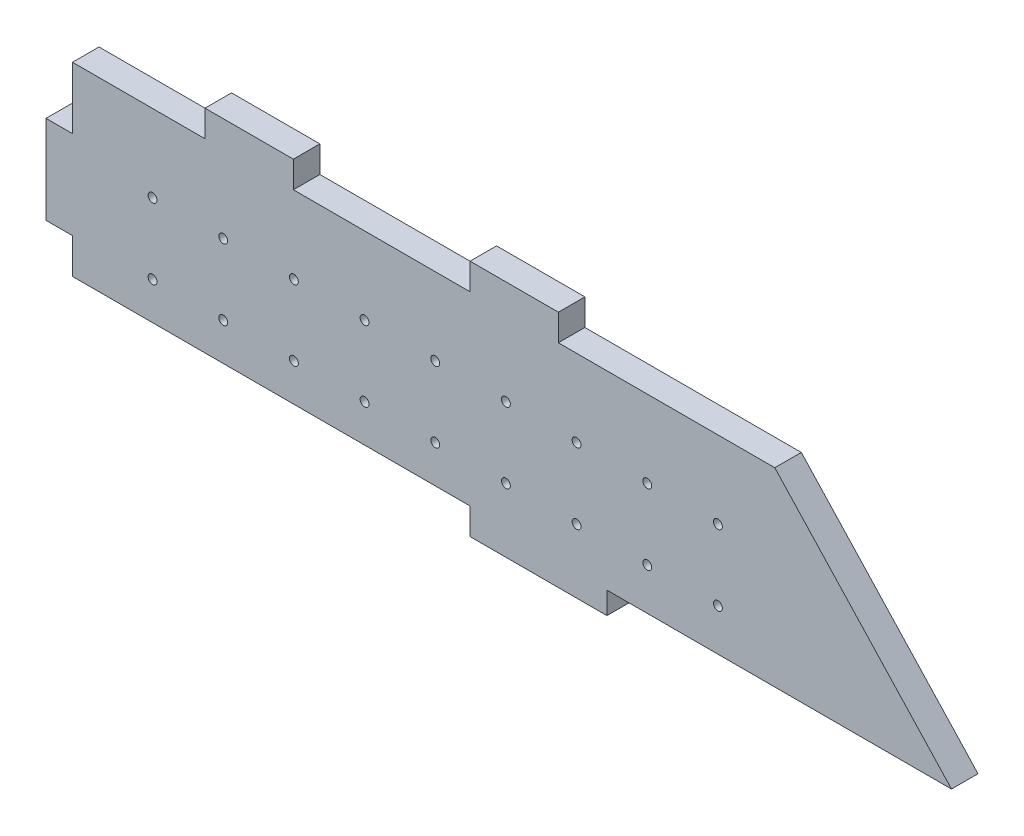
SolidWorks part; units mm, degrees
ref_plane "Plan de face" through (0, 0, 0) normal (0, 0, 1) x (1, 0, 0)
ref_plane "Plan de dessus" through (0, 0, 0) normal (0, 1, 0) x (1, 0, 0)
ref_plane "Plan de droite" through (0, 0, 0) normal (1, 0, 0) x (0, 0, -1)
sketch "Esquisse1" plane through (0, 0, 0) normal (0, 0, 1) x (1, 0, 0)
  line L1 (0, 0) -> (-199, 0)
  line L2 (0, 0) -> (0, 48)
  line L3 (0, 48) -> (-199, 48)
  line L4 (-199, 0) -> (-199, 48)
  dimension "D1" = 48
  dimension "D2" = 199
extrude "Boss.-Extru.1" add sketch "Esquisse1" along normal blind 6
sketch "Esquisse2" plane through (0, 48, 0) normal (0, 1, 0) x (1, 0, 0)
  line L0 (0, -6) -> (-199, -6) construction
  line L1 (-89, -6) -> (-109, -6)
  line L2 (-89, -6) -> (-89, 0)
  line L3 (-89, 0) -> (-109, 0)
  line L4 (-109, -6) -> (-109, 0)
  line L5 (0, 0) -> (-199, 0) construction
  line L6 (-199, -6) -> (-199, 0) construction
  line L7 (-149, -6) -> (-169, -6)
  line L8 (-149, -6) -> (-149, 0)
  line L9 (-149, 0) -> (-169, 0)
  line L10 (-169, -6) -> (-169, 0)
  dimension "D1" = 20
  dimension "D2" = 20
  dimension "D3" = 40
  dimension "D4" = 30
extrude "Boss.-Extru.2" add sketch "Esquisse2" along normal blind 6
sketch "Esquisse3" plane through (-199, 0, 0) normal (-1, 0, 0) x (0, 0, 1)
  line L1 (6, 48) -> (6, 0) construction
  line L2 (6, 34) -> (0, 34)
  line L3 (6, 34) -> (6, 14)
  line L4 (6, 14) -> (0, 14)
  line L6 (0, 34) -> (0, 14)
  line L7 (0, 48) -> (0, 0) construction
  line L8 (6, 48) -> (0, 48) construction
  dimension "D1" = 20
  dimension "D2" = 14
extrude "Boss.-Extru.3" add sketch "Esquisse3" along normal blind 6
sketch "Esquisse4" plane through (0, 0, 6) normal (0, 0, 1) x (1, 0, 0)
  line L1 (0, 0) -> (-78, 0)
  line L2 (0, 0) -> (0, 5)
  line L3 (0, 5) -> (-78, 5)
  line L4 (-78, 0) -> (-78, 5)
  dimension "D1" = 5
  dimension "D2" = 78
extrude "Enlèv. mat.-Extru.1" cut sketch "Esquisse4" against normal through all
sketch "Esquisse5" plane through (0, 0, 6) normal (0, 0, 1) x (1, 0, 0)
  line L0 (0, 48) -> (-40, 48)
  line L1 (0, 48) -> (-89, 48) construction
  line L2 (-40, 48) -> (0, 5)
  line L3 (0, 5) -> (0, 48)
  dimension "D1" = 159
extrude "Enlèv. mat.-Extru.2" cut sketch "Esquisse5" against normal through all
sketch "Esquisse6" plane through (0, 0, 6) normal (0, 0, 1) x (1, 0, 0)
  line L0 (-199, 0) -> (-78, 0) construction
  line L1 (-199, 14) -> (-199, 0) construction
  line L2 (-199, 48) -> (-199, 34) construction
  line L3 (-148.88, 14.5) -> (-164.88, 14.5) construction
  line L5 (-199, 0) -> (-78, 0) construction
  circle A0 centre (-148.88, 14.5) radius 1.005
  circle A1 centre (-148.88, 30.5) radius 1.005
  circle A2 centre (-132.88, 14.5) radius 1.005
  circle A3 centre (-132.88, 30.5) radius 1.005
  circle A4 centre (-116.88, 14.5) radius 1.005
  circle A5 centre (-116.88, 30.5) radius 1.005
  circle A6 centre (-100.88, 14.5) radius 1.005
  circle A7 centre (-100.88, 30.5) radius 1.005
  circle A8 centre (-84.88, 14.5) radius 1.005
  circle A9 centre (-84.88, 30.5) radius 1.005
  circle A10 centre (-68.88, 14.5) radius 1.005
  circle A11 centre (-68.88, 30.5) radius 1.005
  circle A12 centre (-52.88, 14.5) radius 1.005
  circle A13 centre (-52.88, 30.5) radius 1.005
  circle A14 centre (-164.88, 14.5) radius 1.005
  circle A15 centre (-164.88, 30.5) radius 1.005
  circle A16 centre (-180.88, 14.5) radius 1.005
  circle A17 centre (-180.88, 30.5) radius 1.005
  dimension "D1" = 2.01
  dimension "D2" = 2.01
  dimension "D3" = 2.01
  dimension "D4" = 2.01
  dimension "D12" = 50.12
  dimension "D16" = 14.5
  dimension "D17" = 14.5
  dimension "D18" = 16
  dimension "D5" = 16
  dimension "D6" = 16
  dimension "D7" = 16
  dimension "D8" = 16
  dimension "D9" = 14.5
  dimension "D10" = 50.12
  dimension "D11" = 14.5
  dimension "D15" = 16
  dimension "D13" = 6
  dimension "D14" = 3
extrude "Enlèv. mat.-Extru.3" cut sketch "Esquisse6" against normal through all
sketch "Esquisse7" plane through (0, 0, 0) normal (0, 0, -1) x (-1, 0, 0)
  line L0 (199, 0) -> (78, 0) construction
  circle A0 centre (180.88, 14.5) radius 2
  circle A1 centre (180.88, 30.5) radius 2
  circle A2 centre (164.88, 14.5) radius 2
  circle A3 centre (164.88, 30.5) radius 2
  circle A4 centre (148.88, 14.5) radius 2
  circle A5 centre (148.88, 30.5) radius 2
  circle A6 centre (132.88, 14.5) radius 2
  circle A7 centre (132.88, 30.5) radius 2
  circle A8 centre (116.88, 14.5) radius 2
  circle A9 centre (116.88, 30.5) radius 2
  circle A10 centre (100.88, 14.5) radius 2
  circle A11 centre (100.88, 30.5) radius 2
  circle A12 centre (84.88, 14.5) radius 2
  circle A13 centre (84.88, 30.5) radius 2
  circle A14 centre (68.88, 14.5) radius 2
  circle A15 centre (68.88, 30.5) radius 2
  circle A16 centre (52.88, 14.5) radius 2
  circle A17 centre (52.88, 30.5) radius 2
  dimension "D1" = 4
  dimension "D2" = 4
  dimension "D4" = 14.5
  dimension "D5" = 16
  dimension "D3" = 9
extrude "Enlèv. mat.-Extru.4" cut sketch "Esquisse7" against normal blind 3
sketch "Esquisse8" plane through (0, 0, 6) normal (0, 0, 1) x (1, 0, 0)
  line L1 (-199, 0) -> (-109, 0)
  line L2 (-199, 0) -> (-199, 6)
  line L3 (-199, 6) -> (-109, 6)
  line L4 (-109, 0) -> (-109, 6)
  dimension "D1" = 6
  dimension "D2" = 90
extrude "Enlèv. mat.-Extru.5" cut sketch "Esquisse8" against normal through all
